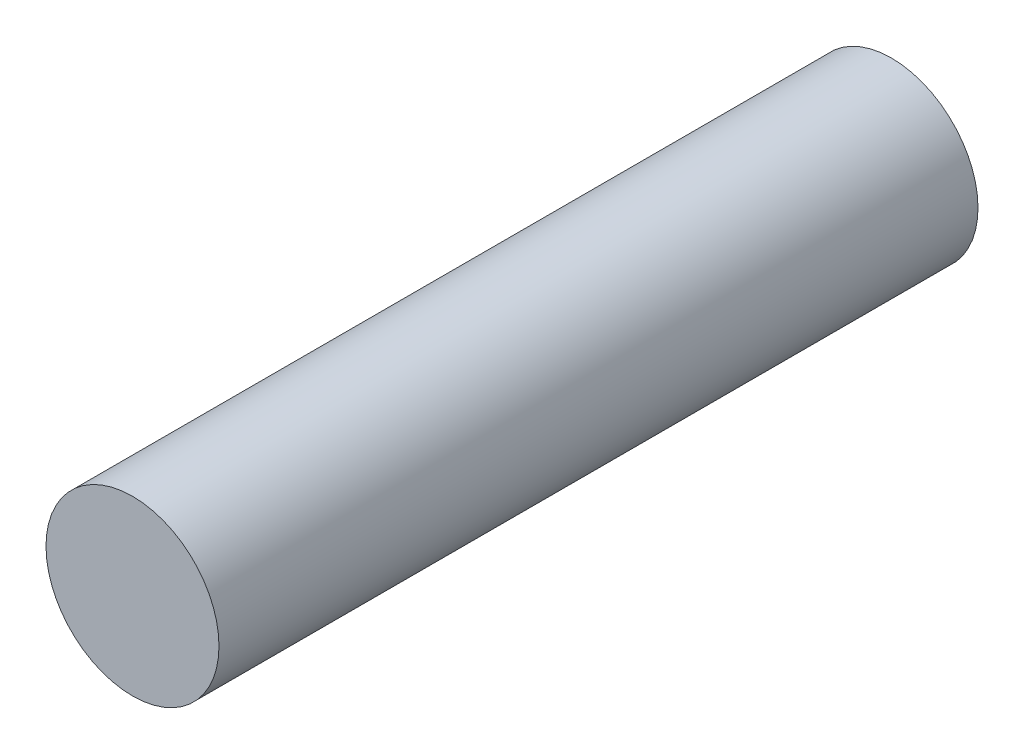
SolidWorks part; units mm, degrees
ref_plane "Front Plane" through (0, 0, 0) normal (0, 0, 1) x (1, 0, 0)
ref_plane "Top Plane" through (0, 0, 0) normal (0, 1, 0) x (1, 0, 0)
ref_plane "Right Plane" through (0, 0, 0) normal (1, 0, 0) x (0, 0, -1)
sketch "Sketch1" plane through (0, 0, 0) normal (0, 0, 1) x (1, 0, 0)
  circle A0 centre (0, 0) radius 1.2
  dimension "D1" = 2.4
extrude "Boss-Extrude1" add sketch "Sketch1" along normal blind 10.53
scale "缩放比例1" scale about centroid uniform scaling yes scale factor 2
